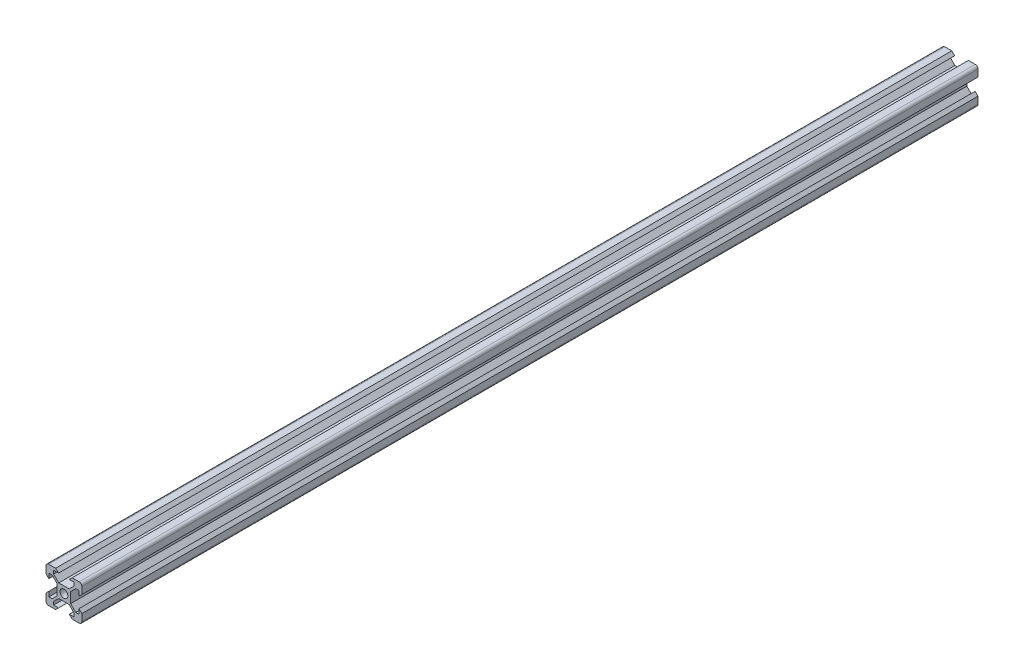
SolidWorks part; units mm, degrees
ref_plane "Front Plane" through (0, 0, 0) normal (0, 0, 1) x (1, 0, 0)
ref_plane "Top Plane" through (0, 0, 0) normal (0, 1, 0) x (1, 0, 0)
ref_plane "Right Plane" through (0, 0, 0) normal (1, 0, 0) x (0, 0, -1)
sketch "Sketch1" plane through (0, 0, 0) normal (0, 0, 1) x (1, 0, 0)
  line L0 (-5.7847, 7.544) -> (-11.512, 13.2713)
  line L1 (-7.544, 7.544) -> (7.544, 7.544)
  line L2 (-7.544, 7.544) -> (-7.544, -7.544)
  line L3 (-7.544, -7.544) -> (7.544, -7.544)
  line L4 (7.544, 7.544) -> (7.544, -7.544)
  line L5 (-7.544, 7.544) -> (7.544, -7.544) construction
  line L6 (-7.544, -7.544) -> (7.544, 7.544) construction
  line L7 (-11.512, 13.2713) -> (-11.512, 16.8)
  line L8 (-11.512, 16.8) -> (-6.052, 16.8)
  line L9 (-6.052, 16.8) -> (-9.252, 20)
  line L10 (-9.252, 20) -> (-17, 20)
  line L11 (-20, 17) -> (-20, 9.252)
  line L12 (-20, 9.252) -> (-16.8, 6.052)
  line L13 (-16.8, 6.052) -> (-16.8, 11.512)
  line L14 (-16.8, 11.512) -> (-13.2713, 11.512)
  line L15 (-13.2713, 11.512) -> (-7.544, 5.7847)
  line L16 (-19.1213, 19.1213) -> (0, 0) construction
  line L17 (13.2713, 11.512) -> (16.8, 11.512)
  line L18 (20, 9.252) -> (20, 17)
  line L19 (17, 20) -> (9.252, 20)
  line L20 (9.252, 20) -> (6.052, 16.8)
  line L21 (6.052, 16.8) -> (11.512, 16.8)
  line L22 (11.512, 16.8) -> (11.512, 13.2713)
  line L23 (11.512, 13.2713) -> (5.7847, 7.544)
  line L24 (7.544, 5.7847) -> (13.2713, 11.512)
  line L25 (16.8, 11.512) -> (16.8, 6.052)
  line L26 (16.8, 6.052) -> (20, 9.252)
  line L27 (19.1213, 19.1213) -> (0, 0) construction
  line L28 (11.512, -13.2713) -> (11.512, -16.8)
  line L29 (9.252, -20) -> (17, -20)
  line L30 (20, -17) -> (20, -9.252)
  line L31 (20, -9.252) -> (16.8, -6.052)
  line L32 (16.8, -6.052) -> (16.8, -11.512)
  line L33 (16.8, -11.512) -> (13.2713, -11.512)
  line L34 (13.2713, -11.512) -> (7.544, -5.7847)
  line L35 (5.7847, -7.544) -> (11.512, -13.2713)
  line L36 (11.512, -16.8) -> (6.052, -16.8)
  line L37 (6.052, -16.8) -> (9.252, -20)
  line L38 (19.1213, -19.1213) -> (0, 0) construction
  line L39 (-13.2713, -11.512) -> (-16.8, -11.512)
  line L40 (-20, -9.252) -> (-20, -17)
  line L41 (-17, -20) -> (-9.252, -20)
  line L42 (-9.252, -20) -> (-6.052, -16.8)
  line L43 (-6.052, -16.8) -> (-11.512, -16.8)
  line L44 (-11.512, -16.8) -> (-11.512, -13.2713)
  line L45 (-11.512, -13.2713) -> (-5.7847, -7.544)
  line L46 (-7.544, -5.7847) -> (-13.2713, -11.512)
  line L47 (-16.8, -11.512) -> (-16.8, -6.052)
  line L48 (-16.8, -6.052) -> (-20, -9.252)
  line L49 (-19.1213, -19.1213) -> (0, 0) construction
  circle A0 centre (0, 0) radius 4.4
  arc A1 (-17, 20) -> (-20, 17) centre (-17, 17) ccw
  arc A2 (20, 17) -> (17, 20) centre (17, 17) ccw
  arc A3 (17, -20) -> (20, -17) centre (17, -17) ccw
  arc A4 (-20, -17) -> (-17, -20) centre (-17, -17) ccw
  point P66 (0, 0)
  dimension "D1" = 8.8
  dimension "D8" = 3
  dimension "D2" = 15.088
  dimension "D3" = 2.488
  dimension "D4" = 8.488
  dimension "D5" = 3.2
  dimension "D6" = 20
  dimension "D7" = 15.2
  dimension "D9" = 4
extrude "Boss-Extrude1" add sketch "Sketch1" along normal mid plane 1000 contours L10 A1 L11 L12 L13 L14 L15 L2 L1 L0 L7 L8 L9 | L18 A2 L19 L20 L21 L22 L23 L1 L4 L24 L17 L25 L26 | L40 A4 L41 L42 L43 L44 L45 L3 L2 L46 L39 L47 L48 | L29 A3 L30 L31 L32 L33 L34 L4 L3 L35 L28 L36 L37 | L4 L1 L2 L3 A0
equation "\"longitud\"= 800"
